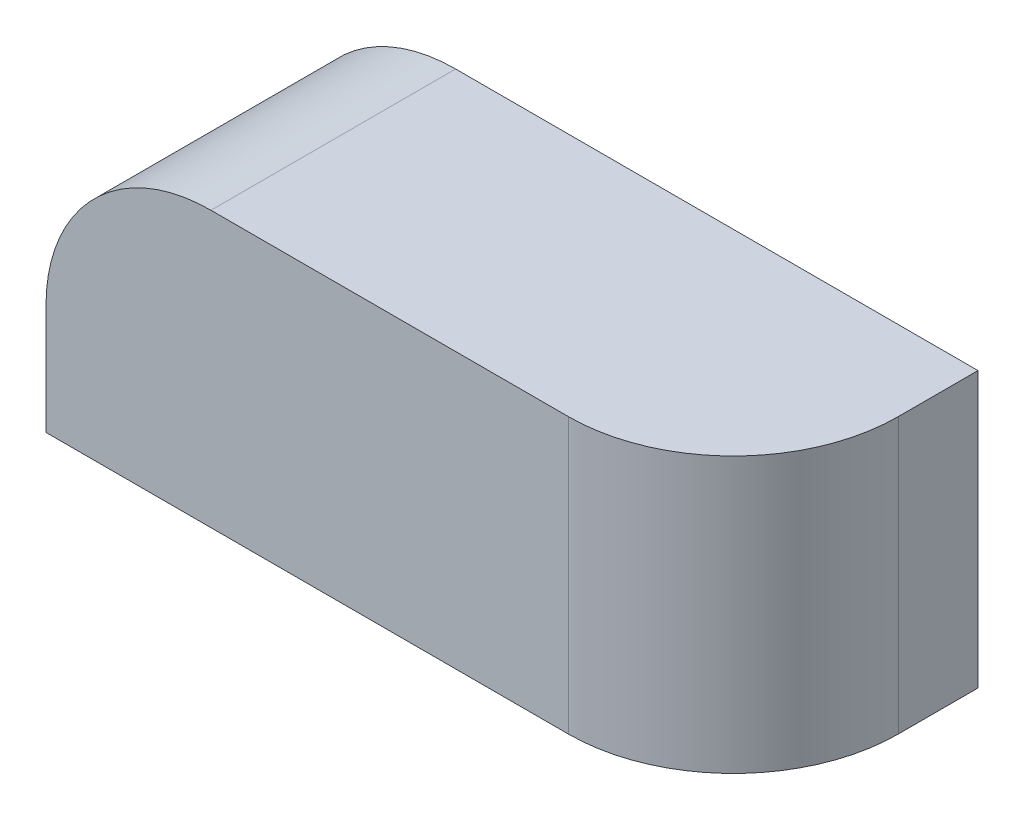
SolidWorks part; units mm, degrees
material "Mahogany"
ref_plane "Front Plane" through (0, 0, 0) normal (0, 0, 1) x (1, 0, 0)
ref_plane "Top Plane" through (0, 0, 0) normal (0, 1, 0) x (1, 0, 0)
ref_plane "Right Plane" through (0, 0, 0) normal (1, 0, 0) x (0, 0, -1)
sketch "Sketch2" plane through (0, 0, 0) normal (0, 0, 1) x (1, 0, 0)
  line L0 (-91.4286, -28.4962) -> (-91.4286, 11.5038)
  line L1 (-31.4286, 71.5038) -> (158.5714, 71.5038)
  line L2 (158.5714, 71.5038) -> (158.5714, -28.4962)
  line L3 (158.5714, -28.4962) -> (-91.4286, -28.4962)
  arc A0 (-91.4286, 11.5038) -> (-31.4286, 71.5038) centre (-31.4286, 11.5038) cw
  point P4 (0, 0)
  dimension "D3" = 60
  dimension "D1" = 100
  dimension "D2" = 250
extrude "Boss-Extrude1" add sketch "Sketch2" against normal blind 89
sketch "Sketch3" plane through (0, 71.5038, 0) normal (0, 1, 0) x (1, 0, 0)
  line L0 (-91.4286, 0) -> (98.5714, 0)
  line L1 (158.5714, 0) -> (-31.4286, 0) construction
  line L2 (158.5714, 89) -> (158.5714, 0) construction
  line L3 (158.5714, 60) -> (158.5714, 89)
  line L4 (158.5714, 89) -> (-91.4286, 89)
  line L5 (-91.4286, 89) -> (-91.4286, 0)
  arc A0 (98.5714, 0) -> (158.5714, 60) centre (98.5714, 60) ccw
  point P9 (0, 0)
  point P14 (158.5714, 57.5213)
  point P15 (140.9978, 17.5736)
  dimension "D1" = 60
extrude "Cut-Extrude1" cut sketch "Sketch3" against normal through all both and the other way through all flip side to cut
shell "Shell1" thickness 3.2
equation "\"round_radii\"= 60"
equation "\"D3@Sketch2\"=\"round_radii\""
equation "\"D1@Sketch3\"=\"round_radii\""
